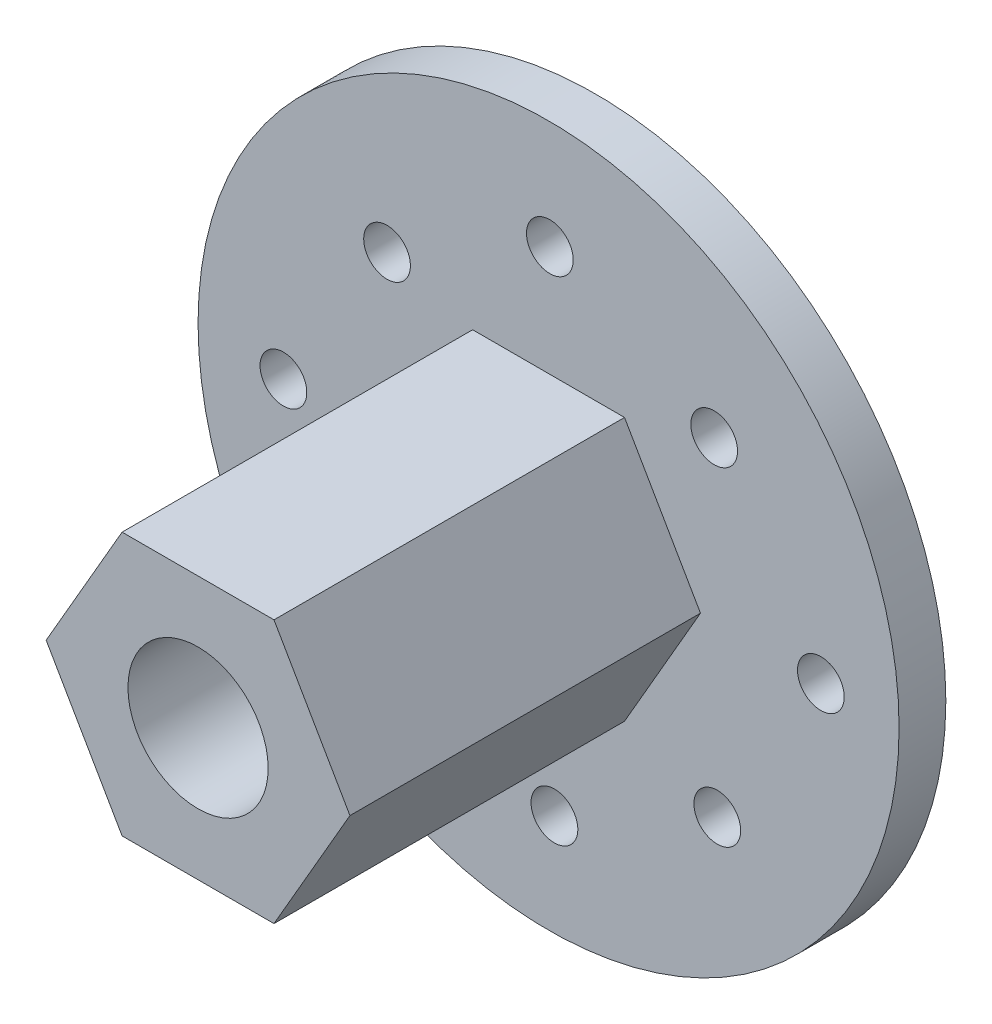
SolidWorks part; units mm, degrees
ref_plane "前视基准面" through (0, 0, 0) normal (0, 0, 1) x (1, 0, 0)
ref_plane "上视基准面" through (0, 0, 0) normal (0, 1, 0) x (1, 0, 0)
ref_plane "右视基准面" through (0, 0, 0) normal (1, 0, 0) x (0, 0, -1)
other "Configuration Table"
sketch "草图1" plane through (0, 0, 0) normal (0, 0, 1) x (1, 0, 0)
  line L1 (6.5, 0) -> (3.25, 5.6292)
  line L2 (3.25, 5.6292) -> (-3.25, 5.6292)
  line L3 (-3.25, 5.6292) -> (-6.5, 0)
  line L4 (-6.5, 0) -> (-3.25, -5.6292)
  line L5 (-3.25, -5.6292) -> (3.25, -5.6292)
  line L6 (3.25, -5.6292) -> (6.5, 0)
  circle A1 centre (0, 0) radius 6.5 construction
  circle A2 centre (0, 0) radius 3
extrude "凸台-拉伸1" add sketch "草图1" along normal blind 15 contours L5 L6 L1 L2 L3 L4 A2
sketch "草图2" plane through (0, 0, 0) normal (0, 0, -1) x (-1, 0, 0)
  circle A0 centre (0, 0) radius 15
  circle A1 centre (0, 0) radius 3
  circle A2 centre (-0.0547, 10.3603) radius 1
  circle A3 centre (6.9122, 6.6679) radius 1
  circle A4 centre (11.3468, -0.2466) radius 1
  circle A5 centre (6.7799, -7.3319) radius 1
  circle A6 centre (-0.2505, -10.6388) radius 1
  circle A7 centre (-7.2201, -7.201) radius 1
  circle A8 centre (-11.6522, -0.0321) radius 1
  circle A9 centre (-7.087, 6.7958) radius 1
extrude "凸台-拉伸2" add sketch "草图2" along normal blind 2
